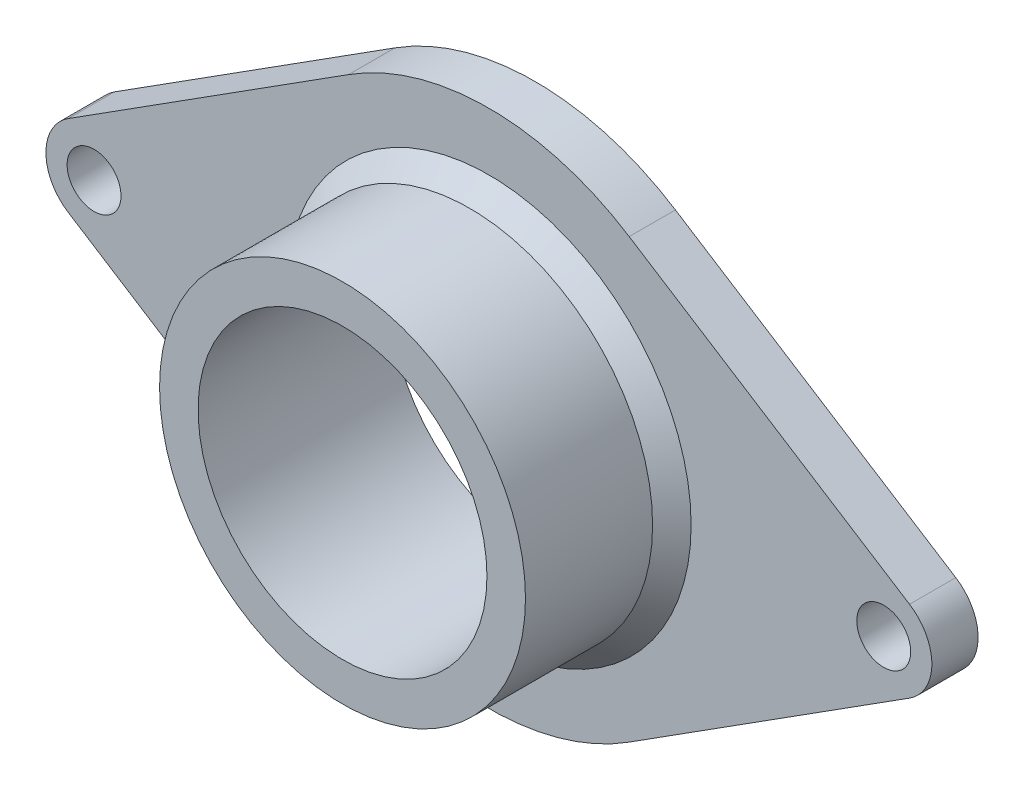
SolidWorks part; units mm, degrees
material "Gray Cast Iron (SN)"
ref_plane "Front Plane" through (0, 0, 0) normal (0, 0, 1) x (1, 0, 0)
ref_plane "Top Plane" through (0, 0, 0) normal (0, 1, 0) x (1, 0, 0)
ref_plane "Right Plane" through (0, 0, 0) normal (1, 0, 0) x (0, 0, -1)
sketch "Sketch1" plane through (0, 0, 0) normal (0, 0, 1) x (1, 0, 0)
  circle A0 centre (0, 0) radius 37.5
  circle A1 centre (0, 0) radius 47.5
  dimension "D1" = 95
  dimension "D2" = 75
extrude "Boss-Extrude1" add sketch "Sketch1" along normal blind 50
sketch "Sketch2" plane through (0, 0, 0) normal (0, 0, -1) x (-1, 0, 0)
  line L2 (36.4251, -56.8284) -> (109.2073, -10.5481)
  line L3 (36.4251, 56.8284) -> (109.2073, 10.5481)
  line L5 (-36.4251, 56.8284) -> (-109.2073, 10.5481)
  line L6 (-36.4251, -56.8284) -> (-109.2073, -10.5481)
  arc A1 (-36.4251, -56.8284) -> (36.4251, -56.8284) centre (0, 0) ccw
  arc A2 (109.2073, -10.5481) -> (109.2073, 10.5481) centre (102.5, 0) ccw
  arc A3 (-109.2073, 10.5481) -> (-109.2073, -10.5481) centre (-102.5, 0) ccw
  arc A4 (36.4251, 56.8284) -> (-36.4251, 56.8284) centre (0, 0) ccw
  circle A5 centre (0, 0) radius 47.5
  dimension "D1" = 135
  dimension "D4" = 25
  dimension "D5" = 25
  dimension "D2" = 95
extrude "Boss-Extrude2" add sketch "Sketch2" against normal blind 12
sketch "Sketch3" plane through (0, 0, 0) normal (0, 0, -1) x (-1, 0, 0)
  circle A0 centre (102.5, 0) radius 7
  circle A1 centre (-102.5, 0) radius 7
  dimension "D1" = 14
  dimension "D2" = 14
extrude "Cut-Extrude1" cut sketch "Sketch3" against normal through all both and the other way through all
chamfer "Chamfer1" distance 5 angle 45 1 edges at (-47.5, 0, 12)
